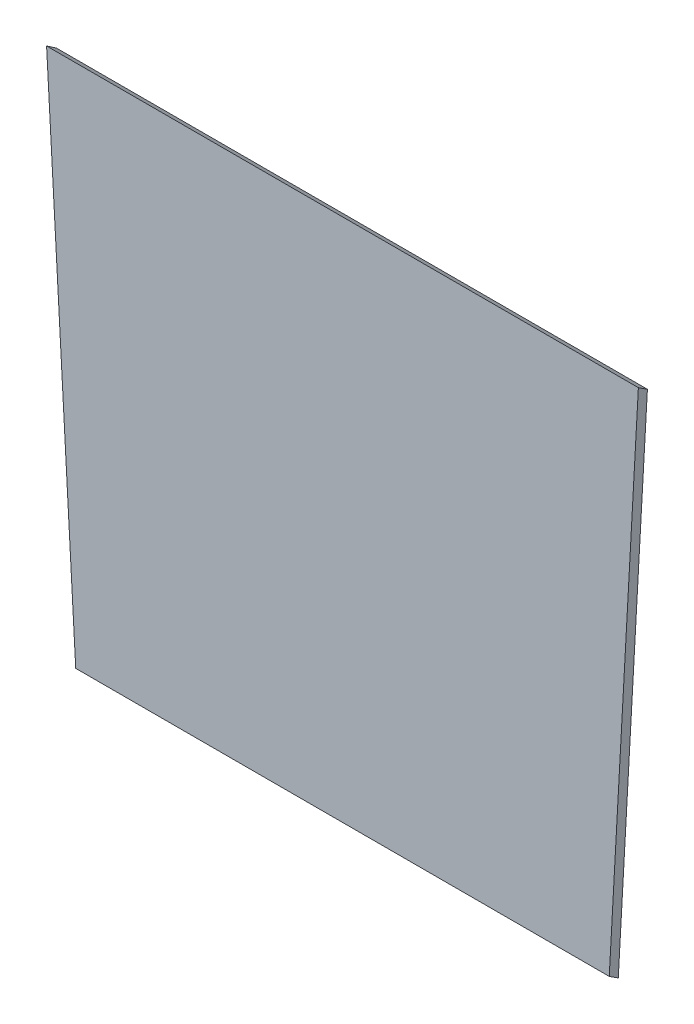
SolidWorks part; units mm, degrees
material "Verre"
ref_plane "Plan de face" through (0, 0, 0) normal (0, 0, 1) x (1, 0, 0)
ref_plane "Plan de dessus" through (0, 0, 0) normal (0, 1, 0) x (1, 0, 0)
ref_plane "Plan de droite" through (0, 0, 0) normal (1, 0, 0) x (0, 0, -1)
sketch "Esquisse1" plane through (0, 0, 0) normal (0, 0, 1) x (1, 0, 0)
  line L0 (-469.9589, 973.2547) -> (1423.1524, 973.2547)
  line L1 (1423.1524, 973.2547) -> (1328.8474, -724.359)
  line L2 (1328.8474, -724.359) -> (-375.6539, -724.359)
  line L3 (-375.6539, -724.359) -> (-469.9589, 973.2547)
  dimension "D1" = 1893.1114
  dimension "D2" = 1704.5012
  dimension "D3" = 1700.2311
extrude "Boss.-Extru.1" add sketch "Esquisse1" along normal blind 30
sketch "Esquisse3" plane through (0, 0, 0) normal (1, 0, 0) x (0, 0, -1)
  line L0 (-30, -724.359) -> (0, -724.359)
  line L1 (0, -724.359) -> (-30, -704.4044)
  line L2 (-30, -724.359) -> (-30, 973.2547) construction
  line L3 (-30, -704.4044) -> (-30, -724.359)
  line L4 (-30, 973.2547) -> (0, 973.2547)
  line L5 (0, 973.2547) -> (0, 953.3001)
  line L6 (0, -724.359) -> (0, 973.2547) construction
  line L7 (0, 953.3001) -> (-30, 973.2547)
  dimension "D1" = 33.63
  dimension "D2" = 33.63
extrude "Enlèv. mat.-Extru.1" cut sketch "Esquisse3" against normal blind 523.145 and the other way blind 1493.145
